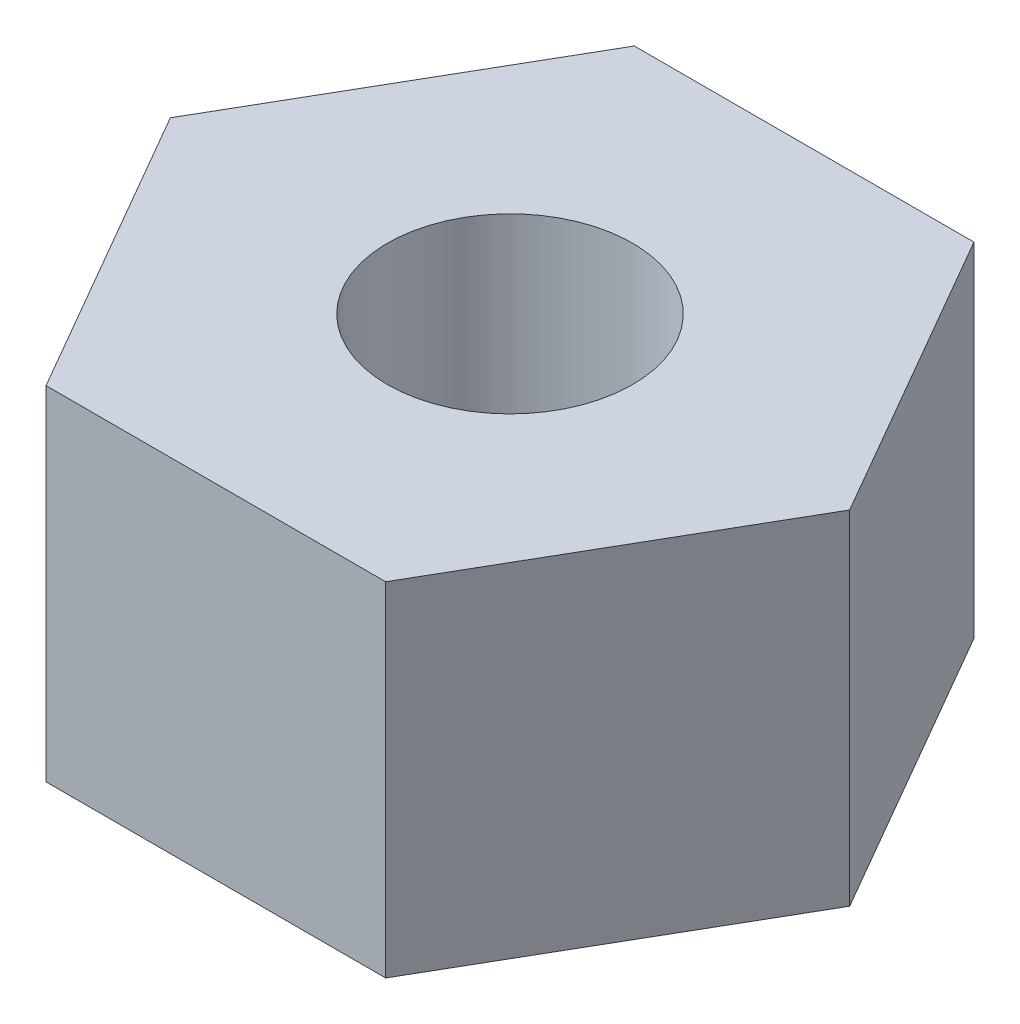
SolidWorks part; units mm, degrees
ref_plane "Front Plane" through (0, 0, 0) normal (0, 0, 1) x (1, 0, 0)
ref_plane "Top Plane" through (0, 0, 0) normal (0, 1, 0) x (1, 0, 0)
ref_plane "Right Plane" through (0, 0, 0) normal (1, 0, 0) x (0, 0, -1)
sketch "Sketch1" plane through (0, 0, 0) normal (0, 1, 0) x (1, 0, 0)
  line L1 (3.4641, 0) -> (1.7321, 3)
  line L2 (1.7321, 3) -> (-1.7321, 3)
  line L3 (-1.7321, 3) -> (-3.4641, 0)
  line L4 (-3.4641, 0) -> (-1.7321, -3)
  line L5 (-1.7321, -3) -> (1.7321, -3)
  line L6 (1.7321, -3) -> (3.4641, 0)
  circle A0 centre (0, 0) radius 3 construction
  circle A1 centre (0, 0) radius 1.25
  dimension "D2" = 2.5
  dimension "D1" = 6
extrude "Boss-Extrude1" add sketch "Sketch1" along normal blind 3.5
